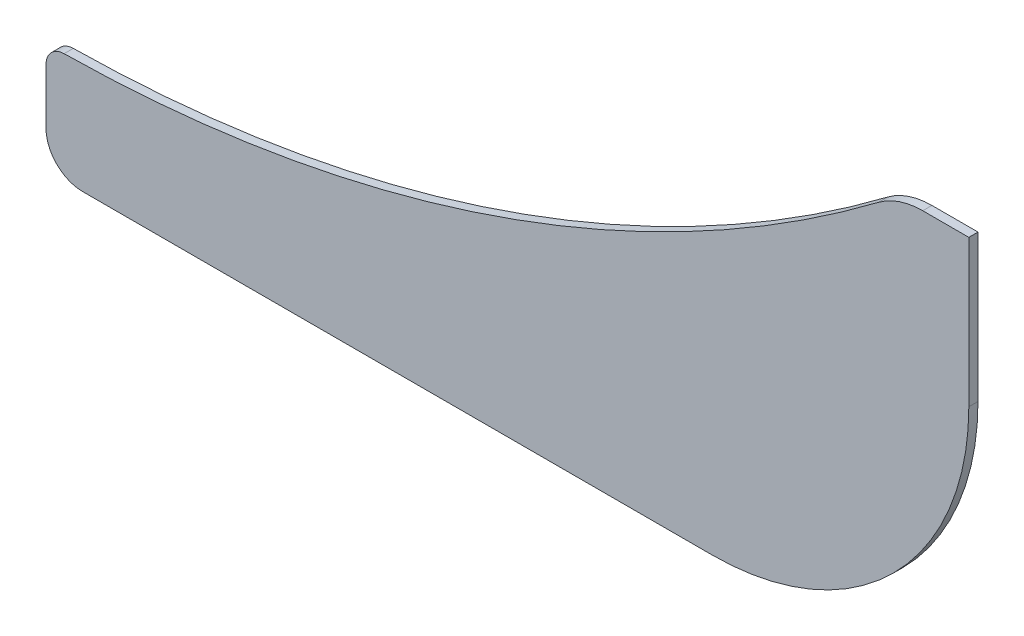
SolidWorks part; units mm, degrees
ref_plane "Front Plane" through (0, 0, 0) normal (0, 0, 1) x (1, 0, 0)
ref_plane "Top Plane" through (0, 0, 0) normal (0, 1, 0) x (1, 0, 0)
ref_plane "Right Plane" through (0, 0, 0) normal (1, 0, 0) x (0, 0, -1)
sketch "Sketch1" plane through (0, 0, 0) normal (0, 0, 1) x (1, 0, 0)
  line L15 (771.9038, 126.6023) -> (771.9038, 164.7023)
  line L17 (-76.2, -210.82) -> (-76.2, -261.62)
  line L20 (0, 0) -> (82.8917, 0) construction
  line L21 (-76.2, -210.82) -> (-250.7577, -210.82) construction
  line L22 (771.9038, 126.6023) -> (907.5478, 126.6023) construction
  line L25 (562.8488, -109.22) -> (562.8488, -7.62)
  line L26 (-50.8, -287.02) -> (385.0488, -287.02)
  line L27 (312.4515, -206.6231) -> (466.4308, -117.7231) construction
  line L28 (443.2209, -118.9957) -> (537.4488, -33.8481) construction
  line L29 (562.8488, -7.62) -> (530.9292, -7.62)
  line L40 (361.6164, -231.6548) -> (133.988, -252.7091) construction
  line L41 (157.3315, -273.5734) -> (-70.4948, -254.7805) construction
  arc A5 (-76.2, -261.62) -> (-50.8, -287.02) centre (-50.8, -261.62) ccw
  arc A6 (-76.2, -210.82) -> (500.3501, -17.8545) centre (-76.2, 746.9827) ccw
  arc A7 (562.8488, -109.22) -> (385.0488, -287.02) centre (385.0488, -109.22) cw
  arc A8 (530.9292, -7.62) -> (500.3501, -17.8545) centre (530.9292, -58.42) ccw
  spline S1 degree 3 poles (155.9851, -273.8364) (157.6707, -273.5362) (155.9614, -273.6091) (154.545, -273.5632) (151.109, -273.588) (146.869, -273.5671) (141.3082, -273.5292) (134.7264, -273.4415) (127.1182, -273.2946) (118.6055, -273.0609) (109.2803, -272.7261) (99.2556, -272.2668) (88.6466, -271.6729) (77.573, -270.9316) (66.1571, -270.0445) (54.5244, -269.0143) (42.7988, -267.8665) (31.1129, -266.6039) (19.6424, -265.3305) (8.5257, -263.8763) (-2.1301, -262.2171) (-12.2969, -260.4475) (-21.892, -258.6332) (-30.8295, -256.8671) (-39.0349, -255.237) (-46.4259, -253.8191) (-52.9324, -252.6861) (-58.4856, -251.9178) (-63.0313, -251.5394) (-66.5319, -251.6451) (-69.0472, -252.1302) (-70.6657, -253.5459) (-70.4472, -255.6917) (-68.9062, -257.778) (-66.3025, -260.229) (-62.4745, -262.9527) (-57.4718, -265.9263) (-51.2992, -269.0205) (-44.0206, -272.1448) (-35.7023, -275.171) (-26.4373, -277.9912) (-16.3291, -280.4924) (-5.4995, -282.5807) (5.9153, -284.1891) (17.7142, -285.2159) (29.7294, -285.7521) (41.8149, -286.0007) (53.9003, -285.9233) (65.8505, -285.5546) (77.5302, -284.9222) (88.8084, -284.06) (99.5605, -283.0113) (109.6699, -281.8268) (119.0235, -280.5542) (127.5233, -279.2575) (135.0819, -277.9817) (141.5945, -276.7938) (147.0755, -275.7324) (151.2398, -274.8709) (154.6131, -274.1873) (155.9851, -273.8364) (157.6707, -273.5362) (155.9614, -273.6091) knots -0.012273 -0.005484 -0.001375 0 0.001366 0.005489 0.012269 0.02165 0.033497 0.04769 0.06403 0.082338 0.102396 0.123959 0.146791 0.170641 0.19524 0.220332 0.245646 0.27091 0.295825 0.31977 0.342911 0.365083 0.386049 0.405629 0.423597 0.43978 0.453966 0.466008 0.475784 0.483219 0.48846 0.492078 0.495706 0.500976 0.508553 0.518608 0.53108 0.545907 0.56292 0.581928 0.60273 0.625094 0.648778 0.673537 0.699099 0.724814 0.750772 0.776731 0.802428 0.827555 0.851851 0.875071 0.896936 0.917223 0.935694 0.952169 0.966419 0.978318 0.987727 0.994516 0.998625 1 1.001366 1.005489 1.012269 only from (157.3315, -273.5734) to (157.3315, -273.5734) construction
  spline S3 degree 3 poles (360.3362, -232.1476) (361.944, -231.5594) (360.2733, -231.9279) (358.8705, -232.1286) (355.491, -232.7497) (351.3118, -233.4654) (345.8288, -234.3937) (339.3319, -235.4503) (331.8137, -236.6267) (323.3898, -237.8749) (314.1481, -239.1645) (304.196, -240.4529) (293.645, -241.7102) (282.6109, -242.9031) (271.2144, -244.0118) (259.5796, -245.0173) (247.8327, -245.923) (236.1052, -246.7089) (224.5878, -247.4466) (213.3874, -247.9449) (202.6055, -248.1613) (192.2857, -248.184) (182.5214, -248.0635) (173.413, -247.8762) (165.0492, -247.6957) (157.5243, -247.5827) (150.9198, -247.5968) (145.3176, -247.8045) (140.7752, -248.2212) (137.3462, -248.9332) (134.9534, -249.8477) (133.6053, -251.5229) (134.1931, -253.5982) (136.0729, -255.3852) (139.0627, -257.3468) (143.3055, -259.3644) (148.7486, -261.4241) (155.3647, -263.3995) (163.0752, -265.2124) (171.7927, -266.7481) (181.4066, -267.9166) (191.7956, -268.6246) (202.8233, -268.8006) (214.344, -268.4024) (226.142, -267.3648) (238.0677, -265.8064) (250.0128, -263.9526) (261.9011, -261.7778) (273.6057, -259.3395) (284.9982, -256.6886) (295.9553, -253.8811) (306.362, -250.9812) (316.1121, -248.0592) (325.1026, -245.1817) (333.2481, -242.4287) (340.4703, -239.8598) (346.6777, -237.559) (351.8912, -235.562) (355.8426, -233.9905) (359.046, -232.7314) (360.3362, -232.1476) (361.944, -231.5594) (360.2733, -231.9279) knots -0.012273 -0.005484 -0.001375 0 0.001366 0.005489 0.012269 0.02165 0.033497 0.04769 0.06403 0.082338 0.102396 0.123959 0.146791 0.170641 0.19524 0.220332 0.245646 0.27091 0.295825 0.31977 0.342911 0.365083 0.386049 0.405629 0.423597 0.43978 0.453966 0.466008 0.475784 0.483219 0.48846 0.492078 0.495706 0.500976 0.508553 0.518608 0.53108 0.545907 0.56292 0.581928 0.60273 0.625094 0.648778 0.673537 0.699099 0.724814 0.750772 0.776731 0.802428 0.827555 0.851851 0.875071 0.896936 0.917223 0.935694 0.952169 0.966419 0.978318 0.987727 0.994516 0.998625 1 1.001366 1.005489 1.012269 only from (361.6164, -231.6548) to (361.6164, -231.6548) construction
  spline S8 degree 3 poles (155.9851, -273.8364) (157.6707, -273.5362) (155.9614, -273.6091) (154.545, -273.5632) (151.109, -273.588) (146.869, -273.5671) (141.3082, -273.5292) (134.7264, -273.4415) (127.1182, -273.2946) (118.6055, -273.0609) (109.2803, -272.7261) (99.2556, -272.2668) (88.6466, -271.6729) (77.573, -270.9316) (66.1571, -270.0445) (54.5244, -269.0143) (42.7988, -267.8665) (31.1129, -266.6039) (19.6424, -265.3305) (8.5257, -263.8763) (-2.1301, -262.2171) (-12.2969, -260.4475) (-21.892, -258.6332) (-30.8295, -256.8671) (-39.0349, -255.237) (-46.4259, -253.8191) (-52.9324, -252.6861) (-58.4856, -251.9178) (-63.0313, -251.5394) (-66.5319, -251.6451) (-69.0472, -252.1302) (-70.6657, -253.5459) (-70.4472, -255.6917) (-68.9062, -257.778) (-66.3025, -260.229) (-62.4745, -262.9527) (-57.4718, -265.9263) (-51.2992, -269.0205) (-44.0206, -272.1448) (-35.7023, -275.171) (-26.4373, -277.9912) (-16.3291, -280.4924) (-5.4995, -282.5807) (5.9153, -284.1891) (17.7142, -285.2159) (29.7294, -285.7521) (41.8149, -286.0007) (53.9003, -285.9233) (65.8505, -285.5546) (77.5302, -284.9222) (88.8084, -284.06) (99.5605, -283.0113) (109.6699, -281.8268) (119.0235, -280.5542) (127.5233, -279.2575) (135.0819, -277.9817) (141.5945, -276.7938) (147.0755, -275.7324) (151.2398, -274.8709) (154.6131, -274.1873) (155.9851, -273.8364) (157.6707, -273.5362) (155.9614, -273.6091) knots -0.012273 -0.005484 -0.001375 0 0.001366 0.005489 0.012269 0.02165 0.033497 0.04769 0.06403 0.082338 0.102396 0.123959 0.146791 0.170641 0.19524 0.220332 0.245646 0.27091 0.295825 0.31977 0.342911 0.365083 0.386049 0.405629 0.423597 0.43978 0.453966 0.466008 0.475784 0.483219 0.48846 0.492078 0.495706 0.500976 0.508553 0.518608 0.53108 0.545907 0.56292 0.581928 0.60273 0.625094 0.648778 0.673537 0.699099 0.724814 0.750772 0.776731 0.802428 0.827555 0.851851 0.875071 0.896936 0.917223 0.935694 0.952169 0.966419 0.978318 0.987727 0.994516 0.998625 1 1.001366 1.005489 1.012269 only from (157.3315, -273.5734) to (157.3315, -273.5734) construction
  point P19 (562.8488, -287.02)
  point P39 (157.3315, -273.5734)
  dimension "D2" = 25.4
  dimension "D3" = 50.8
  dimension "D6" = 127
  dimension "D10" = 177.8
  dimension "D11" = 50.8
  dimension "D13" = 38.1
  dimension "D14" = 25.4
  dimension "D4" = 279.4
  dimension "D5" = 287.02
  dimension "D7" = 177.8
  dimension "D8" = 76.2
  dimension "D9" = 562.8488
extrude "Boss-Extrude1" add sketch "Sketch1" along normal blind 6.35
fillet "Fillet1" radius 12.7 1 edges at (-76.2, -210.82, 3.175)
